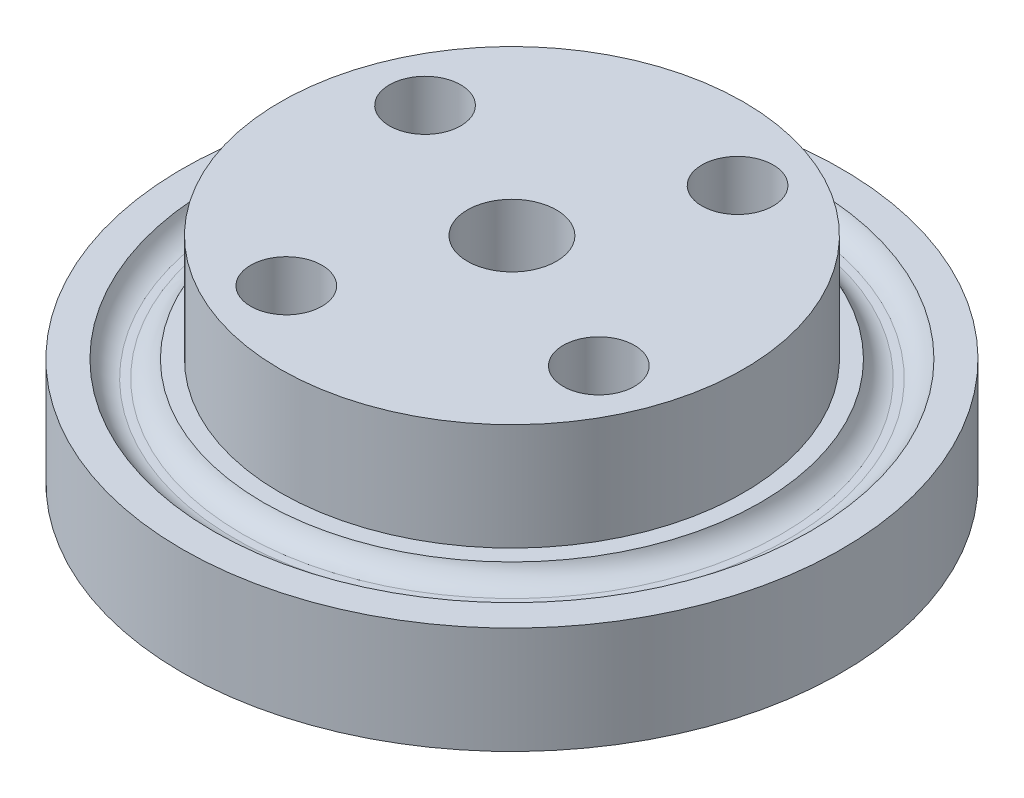
SolidWorks part; units mm, degrees
ref_plane "Спереди" through (0, 0, 0) normal (0, 0, 1) x (1, 0, 0)
ref_plane "Сверху" through (0, 0, 0) normal (0, 1, 0) x (1, 0, 0)
ref_plane "Справа" through (0, 0, 0) normal (1, 0, 0) x (0, 0, -1)
sketch "Эскиз1" plane through (0, 0, 0) normal (0, 1, 0) x (1, 0, 0)
  circle A0 centre (0, 0) radius 18.5
extrude "Вытянуть1" add sketch "Эскиз1" along normal blind 6
sketch "Эскиз2" plane through (0, 0, 0) normal (0, 0, 1) x (1, 0, 0)
  line L1 (-16.2804, 0) -> (-13.2804, 0)
  line L2 (-14.7804, 1.0184) -> (-14.7804, 1.5097) construction
  line L3 (-15.027, 0.9994) -> (-14.5338, 0.9994)
  arc A0 (-16.2804, 0) -> (-15.027, 0.9994) centre (-14.7804, -0.5955) cw
  arc A1 (-14.5338, 0.9994) -> (-13.2804, 0) centre (-14.7804, -0.5955) cw
sketch "Эскиз3" plane through (0, 0, 0) normal (0, -1, 0) x (1, 0, 0)
  circle A0 centre (0, 0) radius 14.7804
sweep "Вырез-По траектории1" cut profiles "Эскиз2" path "Эскиз3"
sketch "Эскиз4" plane through (0, 0, 0) normal (0, 0, 1) x (1, 0, 0)
  line L0 (18.5, 6) -> (-18.5, 6) construction
  line L1 (-16.7515, 6) -> (-13.9538, 6)
  line L2 (-15.3526, 5.0415) -> (-15.3526, 5.3622) construction
  line L3 (-15.5726, 5.0577) -> (-15.1327, 5.0577)
  arc A0 (-16.7515, 6) -> (-15.5726, 5.0577) centre (-15.3526, 6.5415) ccw
  arc A1 (-15.1327, 5.0577) -> (-13.9538, 6) centre (-15.3526, 6.5415) ccw
sketch "Эскиз5" plane through (0, 6, 0) normal (0, 1, 0) x (1, 0, 0)
  circle A0 centre (0, 0) radius 15.3526
sweep "Вырез-По траектории2" cut profiles "Эскиз4" path "Эскиз5"
sketch "Эскиз6" plane through (0, 6, 0) normal (0, 1, 0) x (1, 0, 0)
  circle A0 centre (0, 0) radius 13
extrude "Вытянуть2" add sketch "Эскиз6" along normal blind 6
sketch "Эскиз8" plane through (0, 12, 0) normal (0, 1, 0) x (1, 0, 0)
  circle A0 centre (0, 0) radius 2.5
  circle A1 centre (-3.8944, -8.7708) radius 2
  circle A2 centre (8.7708, -3.8944) radius 2
  circle A3 centre (3.8944, 8.7708) radius 2
  circle A4 centre (-8.7708, 3.8944) radius 2
extrude "Вырез-Вытянуть1" cut sketch "Эскиз8" against normal through all
